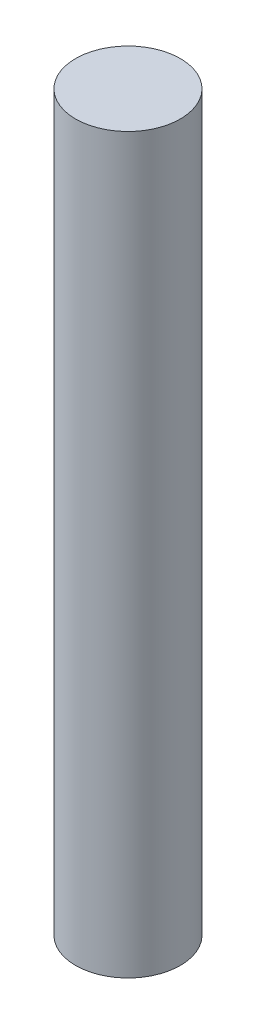
SolidWorks part; units mm, degrees
ref_plane "Front Plane" through (0, 0, 0) normal (0, 0, 1) x (1, 0, 0)
ref_plane "Top Plane" through (0, 0, 0) normal (0, 1, 0) x (1, 0, 0)
ref_plane "Right Plane" through (0, 0, 0) normal (1, 0, 0) x (0, 0, -1)
sketch "Sketch1" plane through (0, 0, 0) normal (0, 1, 0) x (1, 0, 0)
  circle A0 centre (0, 0) radius 0.7937
  dimension "D1" = 1.5875
extrude "Boss-Extrude1" add sketch "Sketch1" along normal blind 11.1125 contours A0
